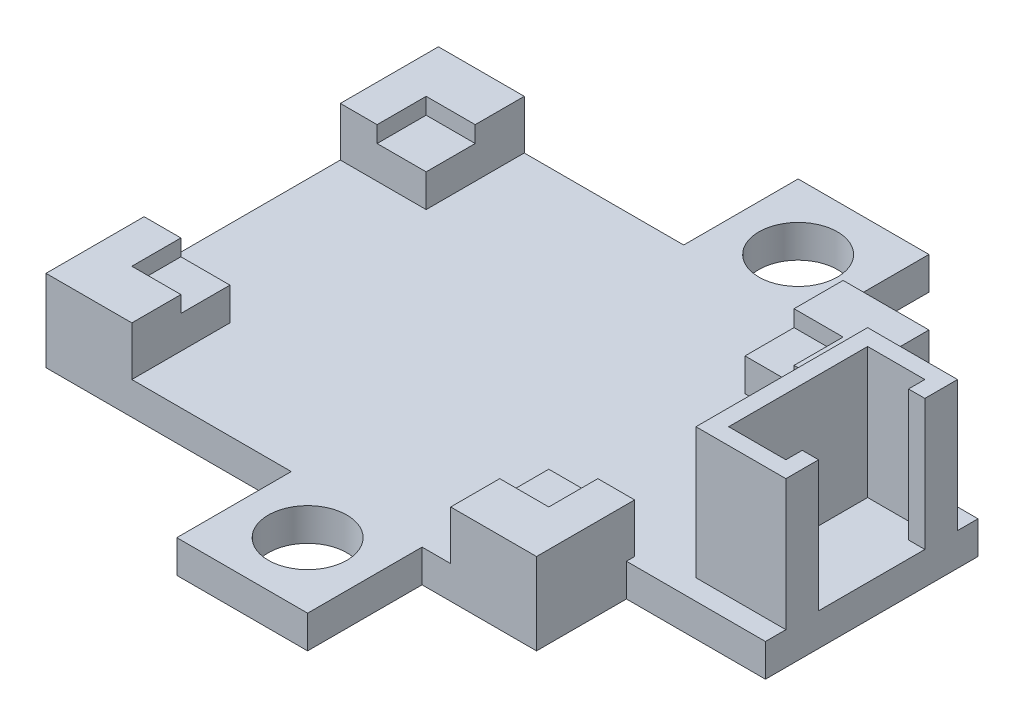
SolidWorks part; units mm, degrees
ref_plane "前视基准面" through (0, 0, 0) normal (0, 0, 1) x (1, 0, 0)
ref_plane "上视基准面" through (0, 0, 0) normal (0, 1, 0) x (1, 0, 0)
ref_plane "右视基准面" through (0, 0, 0) normal (1, 0, 0) x (0, 0, -1)
other "Configuration Table"
sketch "草图1" plane through (0, 0, 0) normal (0, 1, 0) x (1, 0, 0)
  line L1 (-15, 12) -> (15, 12)
  line L2 (-15, 12) -> (-15, -12)
  line L3 (-15, -12) -> (15, -12)
  line L4 (15, 12) -> (15, -12)
  line L5 (-15, 12) -> (15, -12) construction
  line L6 (-15, -12) -> (15, 12) construction
  point P0 (0, 0)
  dimension "D1" = 24
  dimension "D2" = 30
extrude "凸台-拉伸1" add sketch "草图1" along normal blind 2
sketch "草图2" plane through (0, 2, 0) normal (0, 1, 0) x (1, 0, 0)
  line L0 (-15, 12) -> (-15, 6)
  line L1 (-15, 12) -> (-15, -12) construction
  line L2 (-15, 6) -> (-12.75, 6)
  line L3 (-12.75, 6) -> (-12.75, 9)
  line L4 (-12.75, 9) -> (-9.75, 9)
  line L5 (-9.75, 9) -> (-9.75, 12)
  line L6 (15, 12) -> (-15, 12) construction
  line L7 (-9.75, 12) -> (-15, 12)
  line L8 (0, 0) -> (50000, 0) construction
  line L9 (0, 0) -> (0, 50000) construction
  line L10 (9.75, 12) -> (15, 12)
  line L11 (9.75, 9) -> (9.75, 12)
  line L12 (12.75, 9) -> (9.75, 9)
  line L13 (12.75, 6) -> (12.75, 9)
  line L14 (15, 6) -> (12.75, 6)
  line L15 (15, 12) -> (15, 6)
  line L16 (15, -12) -> (15, -6)
  line L17 (15, -6) -> (12.75, -6)
  line L18 (12.75, -6) -> (12.75, -9)
  line L19 (12.75, -9) -> (9.75, -9)
  line L20 (9.75, -9) -> (9.75, -12)
  line L21 (9.75, -12) -> (15, -12)
  line L22 (-9.75, -12) -> (-15, -12)
  line L23 (-9.75, -9) -> (-9.75, -12)
  line L24 (-12.75, -9) -> (-9.75, -9)
  line L25 (-12.75, -6) -> (-12.75, -9)
  line L26 (-15, -6) -> (-12.75, -6)
  line L27 (-15, -12) -> (-15, -6)
  dimension "D1" = 3
  dimension "D2" = 25.5
  dimension "D3" = 18
extrude "凸台-拉伸2" add sketch "草图2" along normal blind 3
sketch "草图3" plane through (0, 2, 0) normal (0, 1, 0) x (1, 0, 0)
  line L0 (-15, 6) -> (-12.75, 6) construction
  line L1 (-12.75, 9) -> (-9.75, 9)
  line L2 (-12.75, 9) -> (-12.75, 6)
  line L3 (-12.75, 6) -> (-9.75, 6)
  line L4 (-9.75, 9) -> (-9.75, 6)
  line L5 (-9.75, 9) -> (-9.75, 12) construction
  line L6 (0, 0) -> (50000, 0) construction
  line L7 (0, 0) -> (0, 50000) construction
  line L8 (9.75, 9) -> (9.75, 6)
  line L9 (12.75, 6) -> (9.75, 6)
  line L10 (12.75, 9) -> (12.75, 6)
  line L11 (12.75, 9) -> (9.75, 9)
  line L12 (12.75, -9) -> (9.75, -9)
  line L13 (12.75, -9) -> (12.75, -6)
  line L14 (12.75, -6) -> (9.75, -6)
  line L15 (9.75, -9) -> (9.75, -6)
  line L16 (-9.75, -9) -> (-9.75, -6)
  line L17 (-12.75, -6) -> (-9.75, -6)
  line L18 (-12.75, -9) -> (-12.75, -6)
  line L19 (-12.75, -9) -> (-9.75, -9)
extrude "凸台-拉伸3" add sketch "草图3" along normal blind 2
sketch "草图4" plane through (15, 0, 0) normal (1, 0, 0) x (0, 0, -1)
  line L0 (12, 5) -> (12, 0) construction
  line L1 (-12, 0) -> (12, 0)
  line L2 (-12, 0) -> (-12, 2)
  line L3 (-12, 2) -> (12, 2)
  line L4 (12, 0) -> (12, 2)
  line L5 (-6, 2) -> (6, 2) construction
extrude "凸台-拉伸4" add sketch "草图4" along normal blind 8.5
sketch "草图5" plane through (0, 2, 0) normal (0, 1, 0) x (1, 0, 0)
  line L0 (18, 5.25) -> (18, -5.25)
  line L1 (19, 4.25) -> (22.5, 4.25)
  line L2 (19, 4.25) -> (19, -4.25)
  line L3 (19, -4.25) -> (22.5, -4.25)
  line L4 (22.5, 4.25) -> (22.5, -4.25)
  line L5 (18, -5.25) -> (23.5, -5.25)
  line L6 (23.5, 5.25) -> (23.5, -5.25)
  line L7 (18, 5.25) -> (23.5, 5.25)
  line L8 (15, 6) -> (15, 12) construction
  line L9 (0, 0) -> (50000, 0) construction
  dimension "D2" = 3
  dimension "D3" = 8.5
  dimension "D4" = 3.5
  dimension "D1" = 1
extrude "凸台-拉伸5" add sketch "草图5" along normal blind 8
sketch "草图6" plane through (0, 10, 0) normal (0, 1, 0) x (1, 0, 0)
  line L6 (22.5, -4.25) -> (22.5, 4.25) construction
  line L7 (22.5, 3.25) -> (23.5, 3.25)
  line L8 (22.5, 3.25) -> (22.5, -3.25)
  line L9 (22.5, -3.25) -> (23.5, -3.25)
  line L10 (23.5, 3.25) -> (23.5, -3.25)
  line L11 (23.5, -5.25) -> (23.5, -12) construction
  line L12 (0, 0) -> (50000, 0) construction
  dimension "D1" = 6.5
extrude "切除-拉伸1" cut sketch "草图6" against normal up to surface (8 mm away) up to face at (8, 2, 0)
sketch "草图7" plane through (0, 2, 0) normal (0, 1, 0) x (1, 0, 0)
  line L0 (15, 12) -> (15, 6) construction
  line L1 (23.5, 12) -> (15, 12)
  line L2 (23.5, 12) -> (23.5, 6.5)
  line L3 (23.5, 6.5) -> (15, 6.5)
  line L4 (15, 12) -> (15, 6.5)
  line L5 (15, -12) -> (15, -6) construction
  line L6 (23.5, -12) -> (15, -12)
  line L7 (23.5, -12) -> (23.5, -6.5)
  line L8 (23.5, -6.5) -> (15, -6.5)
  line L9 (15, -12) -> (15, -6.5)
  line L10 (23.5, 5.25) -> (18, 5.25) construction
  dimension "D1" = 1.25
extrude "切除-拉伸2" cut sketch "草图7" against normal blind 9
sketch "草图8" plane through (0, 2, 0) normal (0, 1, 0) x (1, 0, 0)
  line L0 (9.75, 12) -> (-9.75, 12) construction
  line L1 (0, 12) -> (8, 12)
  line L2 (0, 12) -> (0, 19)
  line L3 (0, 19) -> (8, 19)
  line L4 (8, 12) -> (8, 19)
  line L11 (-15, 12) -> (-15, 6) construction
  line L12 (0, 0) -> (-50000, 0) construction
  line L13 (8, 12) -> (0, 12)
  line L14 (0, 19) -> (0, 12)
  line L15 (8, 19) -> (0, 19)
  line L16 (8, 19) -> (8, 12)
  line L17 (0, 12) -> (8, 12)
  line L18 (0, 12) -> (0, 19)
  line L19 (0, 19) -> (8, 19)
  line L20 (8, 12) -> (8, 19)
  line L21 (8, 12) -> (0, 12)
  line L22 (0, 19) -> (0, 12)
  line L23 (8, 19) -> (0, 19)
  line L24 (8, 19) -> (8, 12)
  line L25 (0, 12) -> (8, 12)
  line L26 (0, 12) -> (0, 19)
  line L27 (0, 19) -> (8, 19)
  line L28 (8, 12) -> (8, 19)
  line L29 (8, 12) -> (0, 12)
  line L30 (0, 19) -> (0, 12)
  line L31 (8, 19) -> (0, 19)
  line L32 (8, 19) -> (8, 12)
  line L33 (0, 12) -> (8, 12)
  line L34 (0, 12) -> (0, 19)
  line L35 (0, 19) -> (8, 19)
  line L36 (8, 12) -> (8, 19)
  line L37 (8, 12) -> (0, 12)
  line L38 (0, 19) -> (0, 12)
  line L39 (8, 19) -> (0, 19)
  line L40 (8, 19) -> (8, 12)
  line L41 (0, -19) -> (8, -12) construction
  line L42 (8, -19) -> (8, -12)
  line L43 (8, -19) -> (0, -19)
  line L44 (0, -19) -> (0, -12)
  line L45 (8, -12) -> (0, -12)
  line L46 (8, -12) -> (8, -19)
  line L47 (0, -19) -> (8, -19)
  line L48 (0, -12) -> (0, -19)
  line L49 (0, -12) -> (8, -12)
  line L50 (8, -19) -> (8, -12)
  line L51 (8, -19) -> (0, -19)
  line L52 (0, -19) -> (0, -12)
  line L53 (8, -12) -> (0, -12)
  line L54 (8, -12) -> (8, -19)
  line L55 (0, -19) -> (8, -19)
  line L56 (0, -12) -> (0, -19)
  line L57 (0, -12) -> (8, -12)
  line L58 (8, -19) -> (8, -12)
  line L59 (8, -19) -> (0, -19)
  line L60 (0, -19) -> (0, -12)
  line L61 (8, -12) -> (0, -12)
  line L62 (8, -12) -> (8, -19)
  line L63 (0, -19) -> (8, -19)
  line L64 (0, -12) -> (0, -19)
  line L65 (0, -12) -> (8, -12)
  line L66 (8, -19) -> (8, -12)
  line L67 (8, -19) -> (0, -19)
  line L68 (0, -19) -> (0, -12)
  line L69 (8, -12) -> (0, -12)
  line L70 (8, -12) -> (8, -19)
  line L71 (0, -19) -> (8, -19)
  line L72 (0, -12) -> (0, -19)
  line L73 (0, -12) -> (8, -12)
  circle A1 centre (4, 15) radius 2.4
  circle A2 centre (4, -15) radius 2.4
  point P21 (4, 19)
  line M16 (9.75, 12) -> (-9.75, 12)
  line M22 (-9.75, -12) -> (9.75, -12)
  dimension "D2" = 4.8
  dimension "D4" = 30
  dimension "D1" = 7
  dimension "D3" = 19
  dimension "D5" = 8
extrude "凸台-拉伸6" add sketch "草图8" against normal up to surface (2 mm away) contours L44 L43 L42 A2 M22 | L4 L3 L2 A1 M16 up to face at (9.625, 0, 0)
